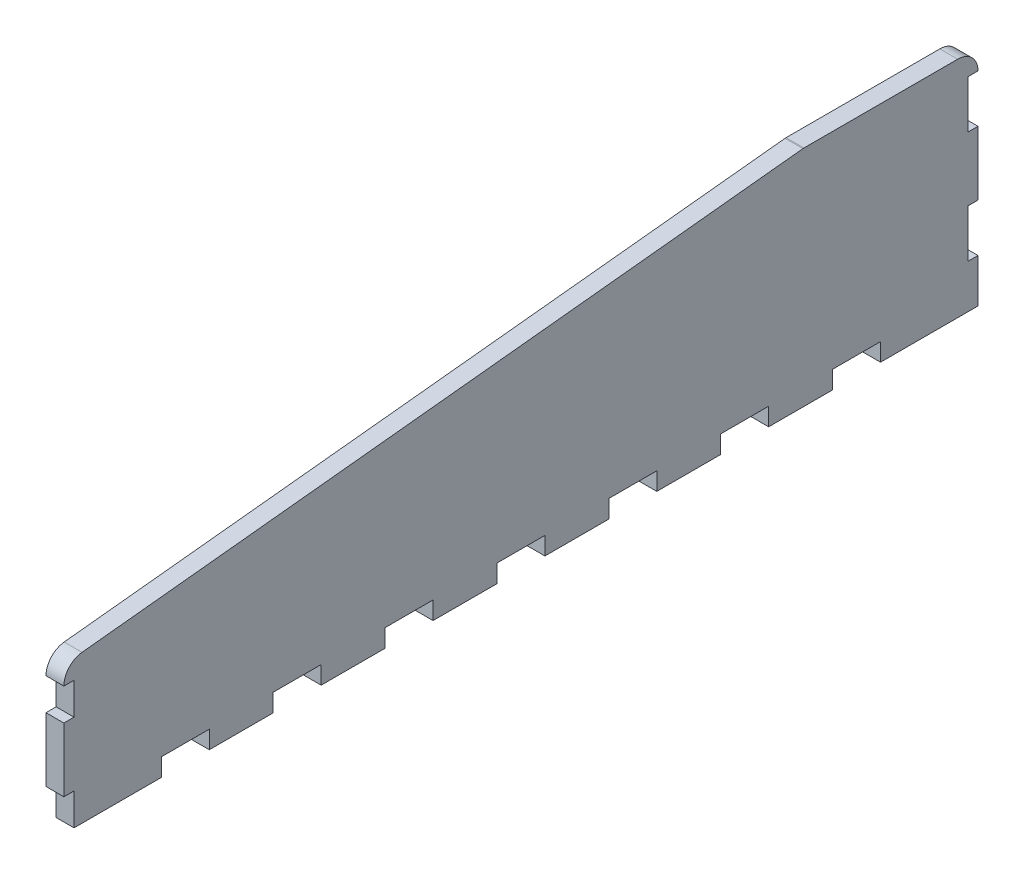
SolidWorks part; units mm, degrees
ref_plane "Front Plane" through (0, 0, 0) normal (0, 0, 1) x (1, 0, 0)
ref_plane "Top Plane" through (0, 0, 0) normal (0, 1, 0) x (1, 0, 0)
ref_plane "Right Plane" through (0, 0, 0) normal (1, 0, 0) x (0, 0, -1)
sketch "Sketch26" plane through (0, 0, 0) normal (1, 0, 0) x (0, 0, -1)
  line L0 (-3.175, -205.3068) -> (-33.6689, -205.3068)
  line L1 (-83.6689, -199.7188) -> (-68.6689, -199.7188)
  line L2 (-3.175, -176.6223) -> (-3.175, -156.6223)
  line L3 (-146.1689, -198.125) -> (-146.1689, -127.985) construction
  line L4 (-289.1629, -175.3068) -> (-289.1629, -195.3068)
  line L5 (-57.959, -135.2888) -> (-283.4766, -158.9916)
  line L6 (-9.525, -135.2723) -> (-57.6454, -135.2723)
  line L7 (-6.35, -191.6223) -> (-6.35, -176.6223)
  line L8 (-118.6689, -199.7188) -> (-103.6689, -199.7188)
  line L9 (-6.35, -191.6223) -> (-3.175, -191.6223)
  line L10 (-118.6689, -205.3068) -> (-138.6689, -205.3068)
  line L11 (-289.1629, -165.3068) -> (-285.9879, -165.3068)
  line L12 (-3.175, -191.6223) -> (-3.175, -205.3068)
  line L13 (-289.1629, -175.3068) -> (-285.9879, -175.3068)
  line L14 (-285.9879, -165.3068) -> (-285.9879, -175.3068)
  line L15 (-83.6689, -205.3068) -> (-103.6689, -205.3068)
  line L16 (-153.6689, -199.7188) -> (-138.6689, -199.7188)
  line L17 (-138.6689, -205.3068) -> (-138.6689, -199.7188)
  line L18 (-118.6689, -199.7188) -> (-118.6689, -205.3068)
  line L19 (-48.6689, -205.3068) -> (-68.6689, -205.3068)
  line L20 (-103.6689, -199.7188) -> (-103.6689, -205.3068)
  line L21 (-83.6689, -199.7188) -> (-83.6689, -205.3068)
  line L22 (-3.175, -176.6223) -> (-6.35, -176.6223)
  line L23 (-68.6689, -199.7188) -> (-68.6689, -205.3068)
  line L24 (-48.6689, -199.7188) -> (-33.6689, -199.7188)
  line L25 (-48.6689, -199.7188) -> (-48.6689, -205.3068)
  line L26 (-3.175, -156.6223) -> (-6.35, -156.6223)
  line L27 (-33.6689, -199.7188) -> (-33.6689, -205.3068)
  line L28 (-258.6689, -199.7188) -> (-258.6689, -205.3068)
  line L29 (-223.6689, -205.3068) -> (-243.6689, -205.3068)
  line L30 (-243.6689, -199.7188) -> (-243.6689, -205.3068)
  line L31 (-243.6689, -199.7188) -> (-258.6689, -199.7188)
  line L32 (-223.6689, -199.7188) -> (-223.6689, -205.3068)
  line L33 (-188.6689, -205.3068) -> (-208.6689, -205.3068)
  line L34 (-208.6689, -199.7188) -> (-208.6689, -205.3068)
  line L35 (-153.6689, -205.3068) -> (-153.6689, -199.7188)
  line L36 (-208.6689, -199.7188) -> (-223.6689, -199.7188)
  line L37 (-188.6689, -199.7188) -> (-188.6689, -205.3068)
  line L38 (-153.6689, -205.3068) -> (-173.6689, -205.3068)
  line L39 (-173.6689, -199.7188) -> (-173.6689, -205.3068)
  line L40 (-173.6689, -199.7188) -> (-188.6689, -199.7188)
  line L41 (-258.6689, -205.3068) -> (-285.9879, -205.3068)
  line L43 (-3.175, -141.6223) -> (-6.35, -141.6223)
  line L44 (-6.35, -156.6223) -> (-6.35, -141.6223)
  line L48 (-289.1629, -195.3068) -> (-285.9879, -195.3068)
  line L51 (-285.9879, -195.3068) -> (-285.9879, -205.3068)
  arc A3 (-283.4766, -158.9916) -> (-289.1629, -165.3068) centre (-282.8129, -165.3068) ccw
  arc A4 (-57.6454, -135.2723) -> (-57.959, -135.2888) centre (-57.6454, -138.2723) ccw
  arc A5 (-3.175, -141.6223) -> (-9.525, -135.2723) centre (-9.525, -141.6223) ccw
  dimension "D2" = 15
  dimension "D3" = 15
  dimension "D4" = 3.175
  dimension "D5" = 10
  dimension "D6" = 3.175
  dimension "D7" = 20
  dimension "D8" = 15
  dimension "D9" = 5.588
  dimension "D10" = 5.588
  dimension "D12" = 3.175
  dimension "D13" = 3.175
  dimension "D14" = 20
  dimension "D15" = 20
  dimension "D16" = 3.175
  dimension "D17" = 3.175
  dimension "D18" = 3.175
  dimension "D19" = 5.588
  dimension "D20" = 5.588
  dimension "D21" = 5.588
  dimension "D22" = 5.588
  dimension "D11" = 3
extrude "Boss-Extrude1" add sketch "Sketch26" along normal blind 5.588 contours A5 L6 A4 L5 A3 L11 L14 L13 L4 L48 L51 L41 L28 L31 L30 L29 L32 L36 L34 L33 L37 L40 L39 L38 L35 L16 L17 L10 L18 L8 L20 L15 L21 L1 L23 L19 L25 L24 L27 L0 L12 L9 L7 L22 L2 L26 L44 L43
